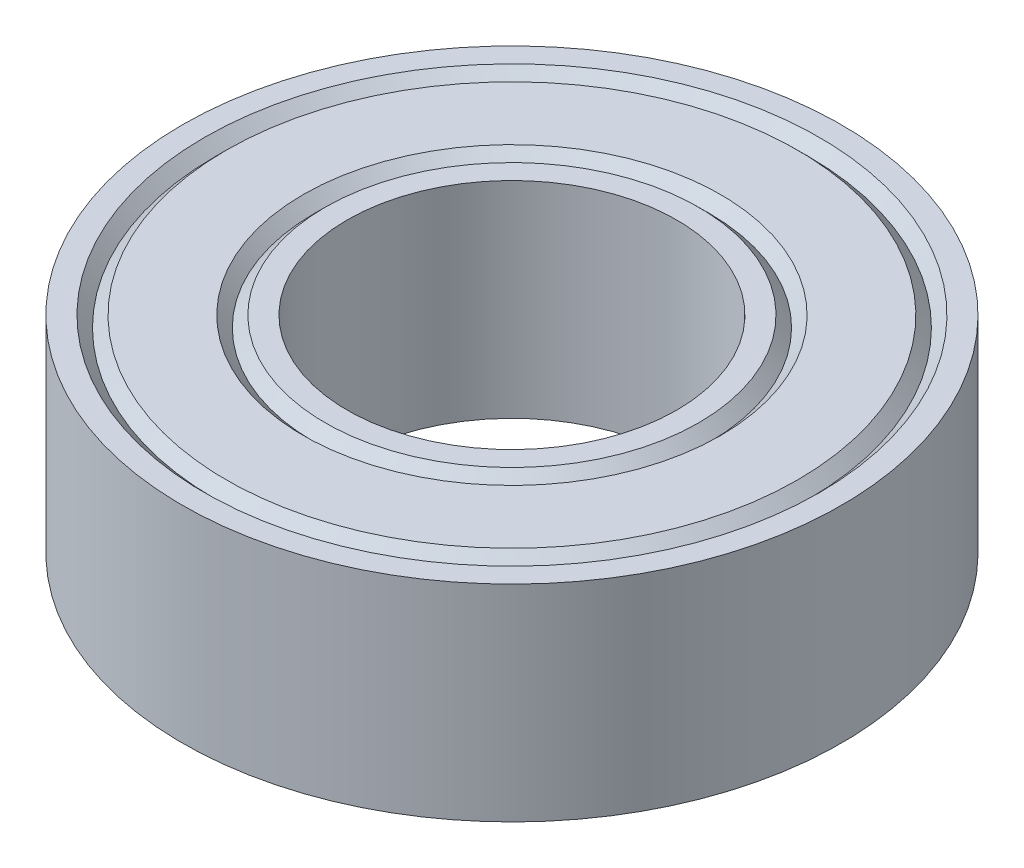
SolidWorks part; units mm, degrees
ref_plane "Front Plane" through (0, 0, 0) normal (0, 0, 1) x (1, 0, 0)
ref_plane "Top Plane" through (0, 0, 0) normal (0, 1, 0) x (1, 0, 0)
ref_plane "Right Plane" through (0, 0, 0) normal (1, 0, 0) x (0, 0, -1)
sketch "Sketch1" plane through (0, 0, 0) normal (0, 0, 1) x (1, 0, 0)
  line L0 (0, 2.5) -> (0, -2.5) construction
  line L1 (-4, 2.5) -> (-4.5333, 2.5)
  line L2 (-4, 2.5) -> (-4, -2.5)
  line L3 (-4, -2.5) -> (-4.5333, -2.5)
  line L4 (-8, 2.5) -> (-8, -2.5)
  line L5 (-7.4667, 2.5) -> (-7.2, 2.2333)
  line L6 (-7.2, 2.2333) -> (-6.9333, 2.5)
  line L7 (-5.0667, 2.5) -> (-4.8, 2.2333)
  line L8 (-4.8, 2.2333) -> (-4.5333, 2.5)
  line L9 (-7.4667, -2.5) -> (-7.2, -2.2333)
  line L10 (-7.2, -2.2333) -> (-6.9333, -2.5)
  line L11 (-5.0667, -2.5) -> (-4.8, -2.2333)
  line L12 (-4.8, -2.2333) -> (-4.5333, -2.5)
  line L13 (-5.0667, -2.5) -> (-6.9333, -2.5)
  line L14 (-7.4667, -2.5) -> (-8, -2.5)
  line L15 (-7.4667, 2.5) -> (-8, 2.5)
  line L16 (-5.0667, 2.5) -> (-6.9333, 2.5)
  line L17 (-7.2, 2.2333) -> (-4.8, 2.2333) construction
  line L18 (-7.2, 2.2333) -> (-7.2, -2.2333) construction
  line L19 (-4.8, -2.2333) -> (-7.2, -2.2333) construction
  line L20 (-4.8, 2.2333) -> (-4.8, -2.2333) construction
  line L21 (-7.2, 0) -> (-6.4, 0) construction
  line L22 (-4.5333, 2.5) -> (-5.0667, 2.5) construction
  line L23 (-6.4, 0) -> (-5.6, 0) construction
  line L24 (-7.2, 0) -> (-8, 0) construction
  line L25 (-5.6, 0) -> (-4.8, 0) construction
  line L26 (-4.8, 0) -> (-4, 0) construction
  dimension "D1" = 5
  dimension "D2" = 8
  dimension "D3" = 16
revolve "Revolve1" add sketch "Sketch1" angle 360 about L0
